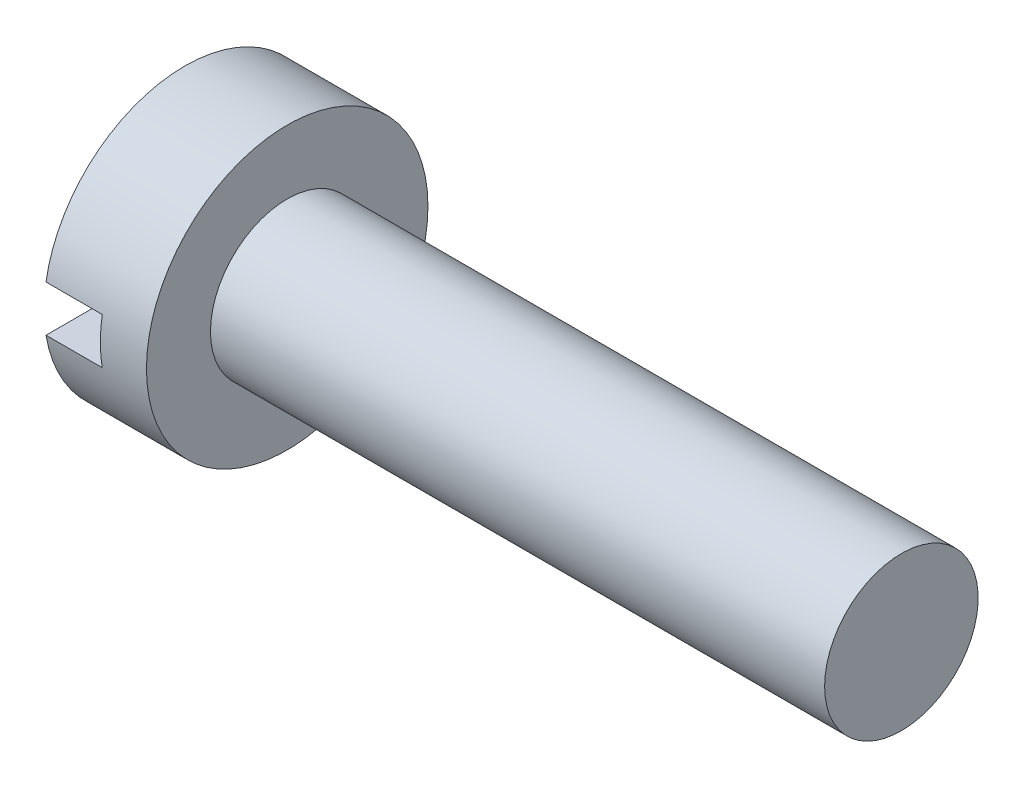
SolidWorks part; units mm, degrees
ref_plane "Plane1" through (0, 0, 0) normal (0, 0, 1) x (1, 0, 0)
ref_plane "Plane2" through (0, 0, 0) normal (0, 1, 0) x (1, 0, 0)
ref_plane "Plane3" through (0, 0, 0) normal (1, 0, 0) x (0, 0, -1)
sketch "BodySke" plane through (0, 0, 0) normal (0, 0, 1) x (1, 0, 0)
  line L0 (2, 1.5) -> (2, 2.75)
  line L1 (0, 0) -> (0, 2.75)
  line L2 (-25.4, 0) -> (127, 0) construction
  line L3 (14, 0) -> (0, 0)
  line L4 (2, 1.5) -> (14, 1.5)
  line L5 (14, 1.5) -> (14, 0)
  line L6 (0, 2.75) -> (2, 2.75)
  line L9 (2.5, 3.0875) -> (2.5, -6.4375) construction
  line L10 (2, 6.35) -> (2, -3.175) construction
  dimension "Length" = 12
  dimension "Head_ht" = 2
  dimension "Advance" = 0.5
  dimension "Thread_nom" = 12
  dimension "Head_dia" = 5.5
  dimension "Diameter" = 3
revolve "Base-Revolve" add sketch "BodySke" angle 360 about L2
cosmetic thread "ThreadCosmetic" parameters "Thread_length"=11, "Thread_minor"=2.459
sketch "Sketch2" plane through (0, 0, 0) normal (1, 0, 0) x (0, 0, -1)
  line L0 (2.75, -0.45) -> (-2.75, -0.45)
  line L1 (2.75, -0.45) -> (2.75, 0.45)
  line L2 (-2.75, 0.45) -> (2.75, 0.45)
  line L3 (-2.75, 0.45) -> (-2.75, -0.45)
  dimension "D1" = 5.5
  dimension "Slot_width" = 0.9
  dimension "D2" = 2.75
  dimension "D3" = 0.45
extrude "Slot" cut sketch "Sketch2" along normal blind 1.1
equation "\"D1@Sketch2\" = \"Head_dia@BodySke\""
equation "\"D2@Sketch2\" = \"D1@Sketch2\" / 2"
equation "\"D3@Sketch2\" = \"Slot_width@Sketch2\" / 2"
equation "\"Thread_length@ThreadCosmetic\" = ((sgn( (\"Length@BodySke\" - \"Advance@BodySke\" * 2.0 ) - \"Thread_nom@BodySke\" )-1)*( (\"Length@BodySke\" - \"Advance@BodySke\"  * 2.0) - \"Thread_nom@BodySke\" ))/-2+ \"Thread_nom@BodySke\""
